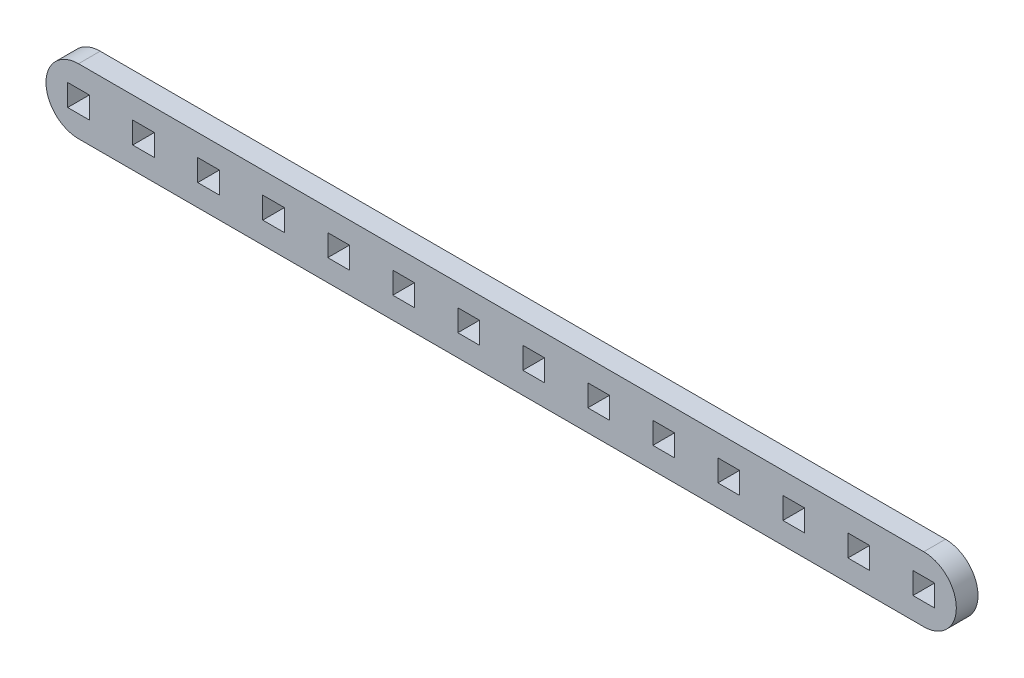
SolidWorks part; units mm, degrees
ref_plane "Alzado" through (0, 0, 0) normal (0, 0, 1) x (1, 0, 0)
ref_plane "Planta" through (0, 0, 0) normal (0, 1, 0) x (1, 0, 0)
ref_plane "Vista lateral" through (0, 0, 0) normal (1, 0, 0) x (0, 0, -1)
sketch "Model" plane through (0, 0, 0) normal (0, 0, 1) x (1, 0, 0)
  line L0 (8.4048, 293.775) -> (8.4048, 290.775)
  line L1 (11.4048, 293.775) -> (8.4048, 293.775)
  line L2 (11.4048, 290.775) -> (11.4048, 293.775)
  line L3 (8.4048, 290.775) -> (11.4048, 290.775)
  line L4 (17.4048, 293.775) -> (17.4048, 290.775)
  line L5 (20.4048, 293.775) -> (17.4048, 293.775)
  line L6 (20.4048, 290.775) -> (20.4048, 293.775)
  line L7 (17.4048, 290.775) -> (20.4048, 290.775)
  line L8 (26.4048, 293.775) -> (26.4048, 290.775)
  line L9 (29.4048, 293.775) -> (26.4048, 293.775)
  line L10 (29.4048, 290.775) -> (29.4048, 293.775)
  line L11 (26.4048, 290.775) -> (29.4048, 290.775)
  line L12 (35.4048, 293.775) -> (35.4048, 290.775)
  line L13 (38.4048, 293.775) -> (35.4048, 293.775)
  line L14 (38.4048, 290.775) -> (38.4048, 293.775)
  line L15 (35.4048, 290.775) -> (38.4048, 290.775)
  line L16 (44.4048, 293.775) -> (44.4048, 290.775)
  line L17 (47.4048, 293.775) -> (44.4048, 293.775)
  line L18 (47.4048, 290.775) -> (47.4048, 293.775)
  line L19 (44.4048, 290.775) -> (47.4048, 290.775)
  line L20 (53.4048, 293.775) -> (53.4048, 290.775)
  line L21 (56.4048, 293.775) -> (53.4048, 293.775)
  line L22 (56.4048, 290.775) -> (56.4048, 293.775)
  line L23 (53.4048, 290.775) -> (56.4048, 290.775)
  line L24 (62.4048, 293.775) -> (62.4048, 290.775)
  line L25 (65.4048, 293.775) -> (62.4048, 293.775)
  line L26 (65.4048, 290.775) -> (65.4048, 293.775)
  line L27 (62.4048, 290.775) -> (65.4048, 290.775)
  line L28 (71.4048, 293.775) -> (71.4048, 290.775)
  line L29 (74.4048, 293.775) -> (71.4048, 293.775)
  line L30 (74.4048, 290.775) -> (74.4048, 293.775)
  line L31 (71.4048, 290.775) -> (74.4048, 290.775)
  line L32 (80.4048, 293.775) -> (80.4048, 290.775)
  line L33 (83.4048, 293.775) -> (80.4048, 293.775)
  line L34 (83.4048, 290.775) -> (83.4048, 293.775)
  line L35 (80.4048, 290.775) -> (83.4048, 290.775)
  line L36 (89.4048, 293.775) -> (89.4048, 290.775)
  line L37 (92.4048, 293.775) -> (89.4048, 293.775)
  line L38 (92.4048, 290.775) -> (92.4048, 293.775)
  line L39 (89.4048, 290.775) -> (92.4048, 290.775)
  line L40 (125.4048, 293.775) -> (125.4048, 290.775)
  line L41 (128.4048, 293.775) -> (125.4048, 293.775)
  line L42 (128.4048, 290.775) -> (128.4048, 293.775)
  line L43 (125.4048, 290.775) -> (128.4048, 290.775)
  line L44 (98.4048, 293.775) -> (98.4048, 290.775)
  line L45 (101.4048, 293.775) -> (98.4048, 293.775)
  line L46 (101.4048, 290.775) -> (101.4048, 293.775)
  line L47 (98.4048, 290.775) -> (101.4048, 290.775)
  line L48 (107.4048, 293.775) -> (107.4048, 290.775)
  line L49 (110.4048, 293.775) -> (107.4048, 293.775)
  line L50 (110.4048, 290.775) -> (110.4048, 293.775)
  line L51 (107.4048, 290.775) -> (110.4048, 290.775)
  line L52 (116.4048, 293.775) -> (116.4048, 290.775)
  line L53 (119.4048, 293.775) -> (116.4048, 293.775)
  line L54 (119.4048, 290.775) -> (119.4048, 293.775)
  line L55 (116.4048, 290.775) -> (119.4048, 290.775)
  line L56 (9.9048, 296.775) -> (126.9048, 296.775)
  line L57 (9.9048, 287.775) -> (126.9048, 287.775)
  arc A0 (9.9048, 296.775) -> (9.9048, 287.775) centre (9.9048, 292.275) ccw
  arc A1 (126.9048, 287.775) -> (126.9048, 296.775) centre (126.9048, 292.275) ccw
extrude "Saliente-Extruir1" add sketch "Model" along normal blind 3
